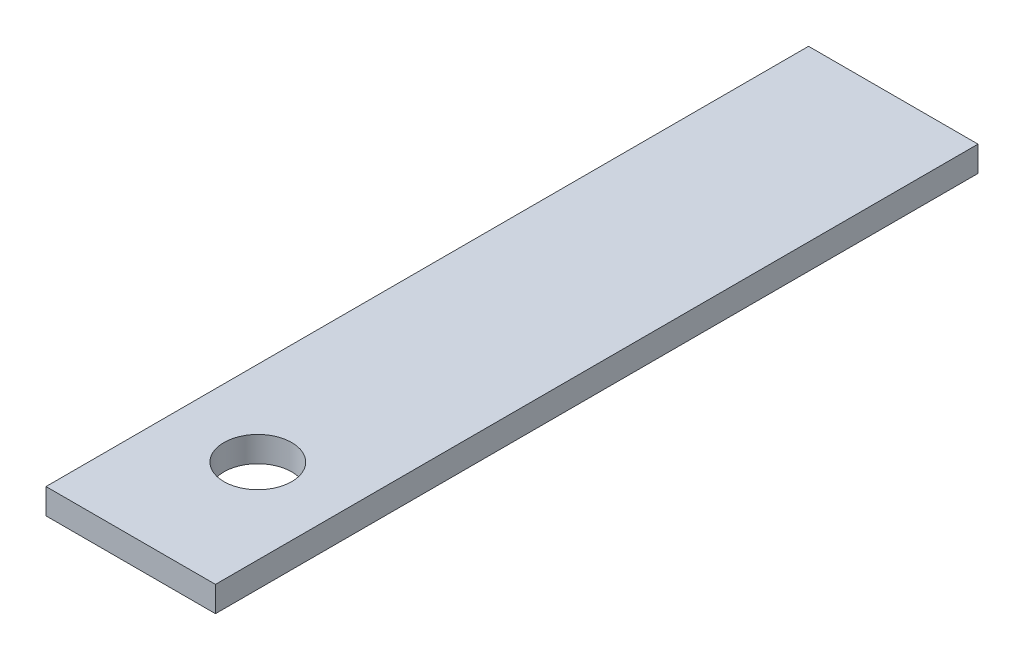
SolidWorks part; units mm, degrees
ref_plane "Front Plane" through (0, 0, 0) normal (0, 0, 1) x (1, 0, 0)
ref_plane "Top Plane" through (0, 0, 0) normal (0, 1, 0) x (1, 0, 0)
ref_plane "Right Plane" through (0, 0, 0) normal (1, 0, 0) x (0, 0, -1)
sketch "Sketch1" plane through (0, 0, 0) normal (0, 1, 0) x (1, 0, 0)
  line L0 (0, -45) -> (0, -30)
  line L1 (-10, 45) -> (10, 45)
  line L2 (-10, 45) -> (-10, -45)
  line L3 (-10, -45) -> (10, -45)
  line L4 (10, 45) -> (10, -45)
  line L5 (-10, 45) -> (10, -45) construction
  line L6 (-10, -45) -> (10, 45) construction
  circle A0 centre (0, -30) radius 4
  point P0 (0, 0)
extrude "Boss-Extrude1" add sketch "Sketch1" along normal blind 3
